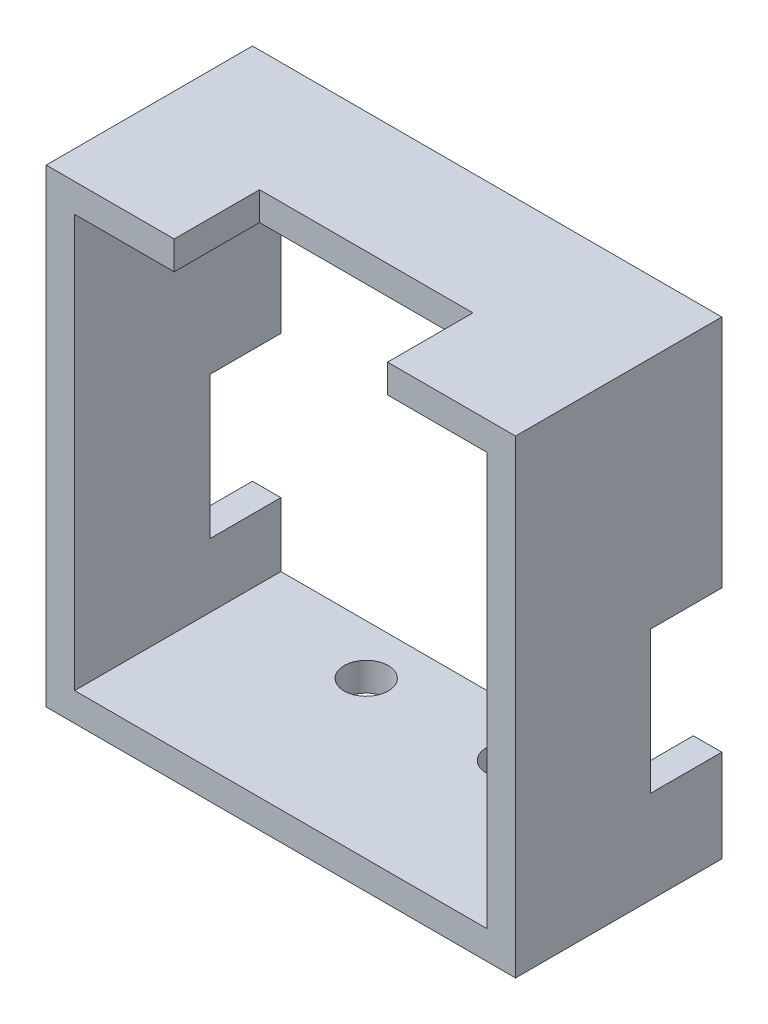
SolidWorks part; units mm, degrees
ref_plane "前视基准面" through (0, 0, 0) normal (0, 0, 1) x (1, 0, 0)
ref_plane "上视基准面" through (0, 0, 0) normal (0, 1, 0) x (1, 0, 0)
ref_plane "右视基准面" through (0, 0, 0) normal (1, 0, 0) x (0, 0, -1)
sketch "草图1" plane through (0, 0, 0) normal (0, 0, 1) x (1, 0, 0)
  line L0 (-2, -2) -> (-2, 31)
  line L1 (0, 0) -> (29, 0)
  line L2 (0, 0) -> (0, 29)
  line L3 (0, 29) -> (29, 29)
  line L4 (29, 0) -> (29, 29)
  line L9 (-2, 31) -> (31, 31)
  line L10 (31, -2) -> (31, 31)
  line L11 (-2, -2) -> (31, -2)
  point P5 (15.5194, 15.4884)
  dimension "D1" = 29
  dimension "D2" = 29
  dimension "D3" = 2
extrude "凸台-拉伸1" add sketch "草图1" along normal blind 14.5
sketch "草图2" plane through (0, -2, 0) normal (0, -1, 0) x (1, 0, 0)
  line L0 (14.5, 14.5) -> (14.5, 4) construction
  line L1 (-2, 14.5) -> (31, 14.5) construction
  line L2 (-2, 0) -> (31, 0) construction
  line L3 (22, 0) -> (22, 4)
  line L4 (22, 0) -> (7, 0)
  line L5 (14.5, 0) -> (14.5, 4) construction
  line L6 (22, 4) -> (7, 4)
  line L7 (7, 0) -> (7, 4)
  line L8 (14.5, 4) -> (14.5, 0) construction
  dimension "D1" = 7.5
  dimension "D2" = 4
sketch "草图3" plane through (0, 31, 0) normal (0, 1, 0) x (1, 0, 0)
  line L0 (14.5, 0) -> (14.5, -8.5) construction
  line L1 (22, 0) -> (7, 0) construction
  line L2 (31, -14.5) -> (-2, -14.5) construction
  line L3 (22, -14.5) -> (22, -8.5)
  line L4 (22, -14.5) -> (7, -14.5)
  line L5 (14.5, -14.5) -> (14.5, -8.5) construction
  line L6 (22, -8.5) -> (7, -8.5)
  line L7 (7, -14.5) -> (7, -8.5)
  line L8 (14.5, -8.5) -> (14.5, -14.5) construction
  dimension "D1" = 7.5
  dimension "D2" = 6
extrude "切除-拉伸2" cut sketch "草图3" against normal up to next
sketch "草图5" plane through (0, -2, 0) normal (0, -1, 0) x (1, 0, 0)
  line L0 (14.5, 14.5) -> (14.5, 0) construction
  line L1 (-2, 14.5) -> (31, 14.5) construction
  line L2 (31, 14.5) -> (31, 0) construction
  circle A0 centre (19.5, 3.5) radius 1.55
  circle A1 centre (9.5, 3.5) radius 1.55
  dimension "D3" = 3.1
  dimension "D1" = 11
  dimension "D2" = 11.5
extrude "切除-拉伸4" cut sketch "草图5" against normal up to next
sketch "草图6" plane through (-2, 0, 0) normal (-1, 0, 0) x (0, 0, 1)
  line L0 (5, 14.5) -> (14.5, 14.5) construction
  line L1 (0, 31) -> (0, -2) construction
  line L2 (14.5, 31) -> (14.5, -2) construction
  line L3 (0, 6.5) -> (5, 6.5) construction
  line L4 (0, 14.5) -> (5, 14.5) construction
  line L5 (0, 6.5) -> (0, 14.5) construction
  line L6 (0, 22.5) -> (5, 22.5) construction
  line L7 (5, 6.5) -> (5, 14.5) construction
  line L8 (0, 14.5) -> (5, 14.5) construction
  line L9 (5, 14.5) -> (5, 22.5) construction
  line L10 (0, 14.5) -> (0, 22.5) construction
  line L12 (0, 14.5) -> (5, 14.5)
  line L13 (0, 14.5) -> (0, 4.5)
  line L14 (0, 4.5) -> (5, 4.5)
  line L15 (5, 14.5) -> (5, 4.5)
  dimension "D1" = 8
  dimension "D2" = 5
  dimension "D3" = 10
extrude "切除-拉伸5" cut sketch "草图6" against normal through all and the other way through all
sketch "草图7" plane through (0, 0, 14.5) normal (0, 0, 1) x (1, 0, 0)
  line L1 (-2, 31) -> (31, 31)
  line L2 (-2, 31) -> (-2, -2)
  line L3 (-2, -2) -> (31, -2)
  line L4 (31, 31) -> (31, -2)
